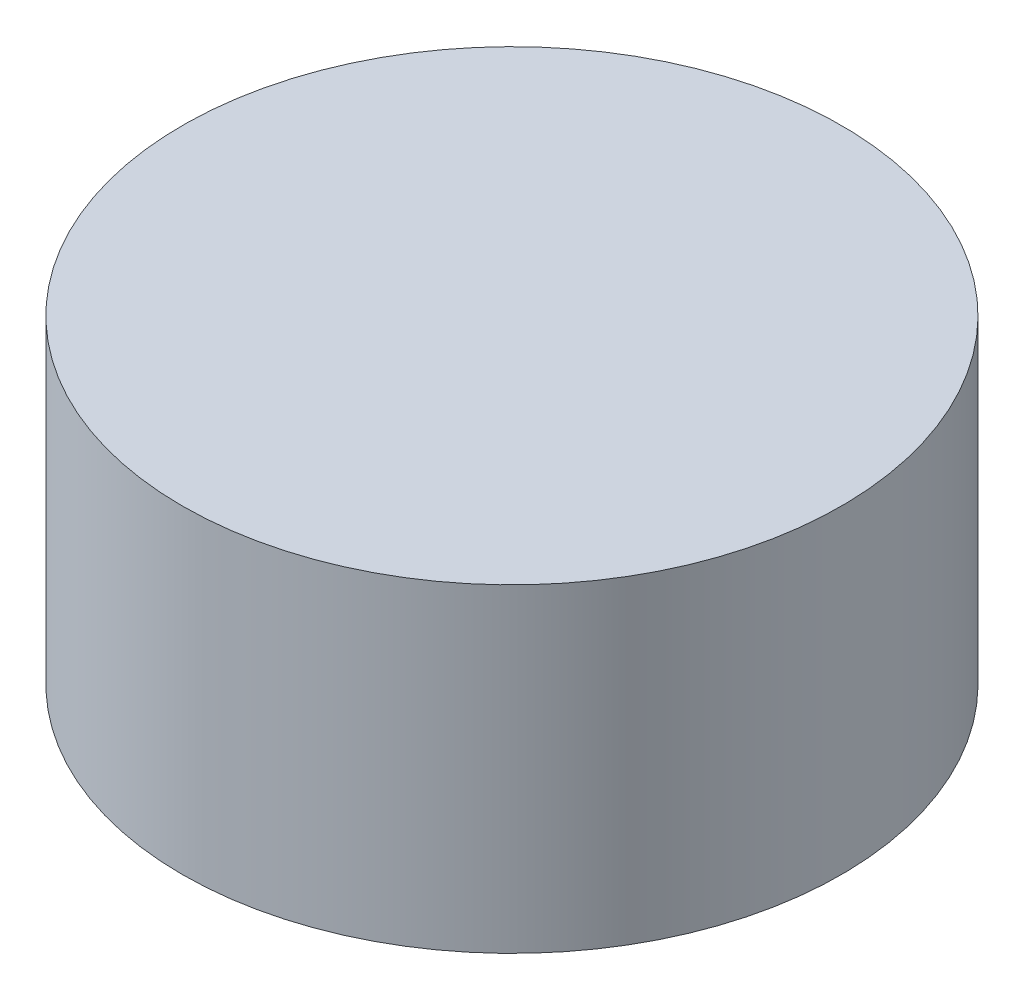
SolidWorks part; units mm, degrees
ref_plane "Front Plane" through (0, 0, 0) normal (0, 0, 1) x (1, 0, 0)
ref_plane "Top Plane" through (0, 0, 0) normal (0, 1, 0) x (1, 0, 0)
ref_plane "Right Plane" through (0, 0, 0) normal (1, 0, 0) x (0, 0, -1)
sketch "Sketch1" plane through (0, 0, 0) normal (0, 1, 0) x (1, 0, 0)
  circle A0 centre (0, 0) radius 10.325
  dimension "D1" = 20.65
extrude "Boss-Extrude1" add sketch "Sketch1" along normal blind 10
